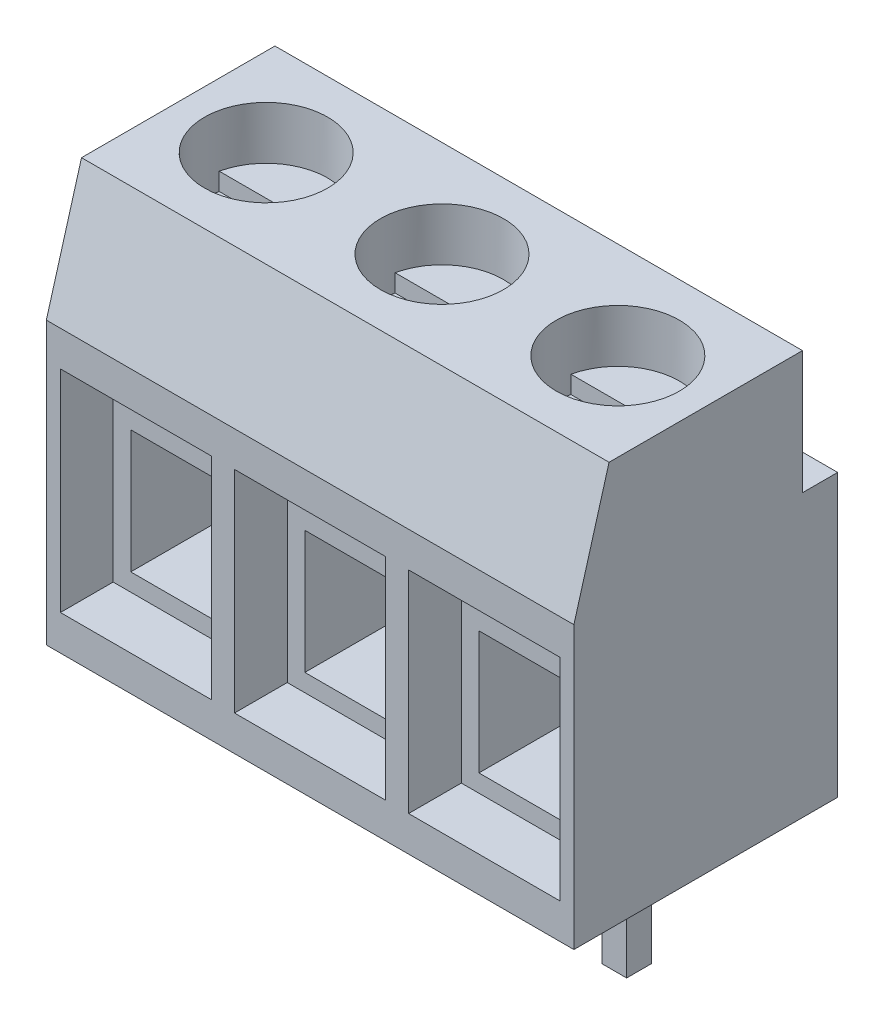
SolidWorks part; units mm, degrees
ref_plane "Front Plane" through (0, 0, 0) normal (0, 0, 1) x (1, 0, 0)
ref_plane "Top Plane" through (0, 0, 0) normal (0, 1, 0) x (1, 0, 0)
ref_plane "Right Plane" through (0, 0, 0) normal (1, 0, 0) x (0, 0, -1)
sketch "Sketch1" plane through (0, 0, 0) normal (0, 1, 0) x (1, 0, 0)
  line L1 (7.5, -3.75) -> (-7.5, -3.75)
  line L2 (7.5, -3.75) -> (7.5, 3.75)
  line L3 (7.5, 3.75) -> (-7.5, 3.75)
  line L4 (-7.5, -3.75) -> (-7.5, 3.75)
  line L5 (7.5, -3.75) -> (-7.5, 3.75) construction
  line L6 (7.5, 3.75) -> (-7.5, -3.75) construction
  point P0 (0, 0)
  dimension "D1" = 15
  dimension "D2" = 7.5
extrude "Boss-Extrude1" add sketch "Sketch1" along normal blind 11.5
sketch "Sketch2" plane through (-7.5, 0, 0) normal (-1, 0, 0) x (0, 0, 1)
  line L1 (-3.75, 11.5) -> (-2.75, 11.5)
  line L2 (-3.75, 11.5) -> (-3.75, 8)
  line L3 (-3.75, 8) -> (-2.75, 8)
  line L4 (-2.75, 11.5) -> (-2.75, 8)
  dimension "D1" = 3.5
  dimension "D2" = 1
extrude "Cut-Extrude1" cut sketch "Sketch2" against normal through all
sketch "Sketch3" plane through (-7.5, 0, 0) normal (-1, 0, 0) x (0, 0, 1)
  line L0 (3.75, 8) -> (2.75, 11.5)
  line L1 (3.75, 11.5) -> (3.75, 0) construction
  line L2 (-2.75, 11.5) -> (3.75, 11.5) construction
  line L4 (-2.75, 8) -> (3.75, 8) construction
  line L5 (2.75, 11.5) -> (3.75, 11.5)
  line L6 (3.75, 11.5) -> (3.75, 8)
  line L7 (-3.75, 8) -> (-2.75, 8) construction
extrude "Cut-Extrude2" cut sketch "Sketch3" against normal through all
sketch "Sketch4" plane through (0, 11.5, 0) normal (0, 1, 0) x (1, 0, 0)
  line L0 (-7.5, 0) -> (-5, 0) construction
  line L1 (-7.5, 2.75) -> (-7.5, -2.75) construction
  line L2 (-5, 0) -> (5, 0) construction
  line L3 (5, 0) -> (7.5, 0) construction
  line L4 (7.5, -2.75) -> (7.5, 2.75) construction
  circle A0 centre (-5, 0) radius 1.75
  circle A1 centre (0, 0) radius 1.75
  circle A2 centre (5, 0) radius 1.75
  dimension "D2" = 3.5
  dimension "D1" = 2.5
extrude "Cut-Extrude3" cut sketch "Sketch4" against normal blind 1.5
sketch "Sketch5" plane through (0, 10, 0) normal (0, 1, 0) x (1, 0, 0)
  line L1 (-6.7093, 0.375) -> (-3.2907, 0.375)
  line L2 (-6.7093, 0.375) -> (-6.7093, -0.375)
  line L3 (-6.7093, -0.375) -> (-3.2907, -0.375)
  line L4 (-3.2907, 0.375) -> (-3.2907, -0.375)
  line L5 (-1.7093, 0.375) -> (1.7093, 0.375)
  line L6 (-1.7093, 0.375) -> (-1.7093, -0.375)
  line L7 (-1.7093, -0.375) -> (1.7093, -0.375)
  line L8 (1.7093, 0.375) -> (1.7093, -0.375)
  line L9 (3.2907, 0.375) -> (6.7093, 0.375)
  line L10 (3.2907, 0.375) -> (3.2907, -0.375)
  line L11 (3.2907, -0.375) -> (6.7093, -0.375)
  line L12 (6.7093, 0.375) -> (6.7093, -0.375)
  circle A1 centre (-5, 0) radius 1.75
  circle A2 centre (-5, 0) radius 1.75
  circle A3 centre (0, 0) radius 1.75
  circle A4 centre (0, 0) radius 1.75
  circle A5 centre (5, 0) radius 1.75
  circle A6 centre (5, 0) radius 1.75
  point P21 (-6.7093, 0)
  circle M14 centre (-5, 0) radius 1.75
  dimension "D4" = 0.75
  dimension "D1" = 0
  dimension "D2" = 0
  dimension "D3" = 0
extrude "Cut-Extrude4" cut sketch "Sketch5" against normal blind 0.5 contours L4 L1 L2 L3 | L2 M14 | L4 M14 | L8 L5 L6 L7 | L8 A4 | L12 L9 L10 L11 | L12 A6 | L10 A6 | L6 A4
sketch "Sketch6" plane through (0, 0, 3.75) normal (0, 0, 1) x (1, 0, 0)
  line L0 (-7.5, 0) -> (7.5, 0) construction
  line L1 (-7.1, 7) -> (-2.8, 7)
  line L2 (-7.1, 7) -> (-7.1, 1)
  line L3 (-7.1, 1) -> (-2.8, 1)
  line L4 (-2.8, 7) -> (-2.8, 1)
  line L5 (-2.15, 7) -> (2.15, 7)
  line L6 (-2.15, 7) -> (-2.15, 1)
  line L7 (-2.15, 1) -> (2.15, 1)
  line L8 (2.15, 7) -> (2.15, 1)
  line L9 (2.8, 7) -> (7.1, 7)
  line L10 (2.8, 7) -> (2.8, 1)
  line L11 (2.8, 1) -> (7.1, 1)
  line L12 (7.1, 7) -> (7.1, 1)
  line L13 (-7.5, 8) -> (-7.5, 0) construction
  line L14 (7.5, 8) -> (7.5, 0) construction
  point P14 (0, 1)
  point P16 (-2.7462, 7)
  point P19 (7.2494, 1)
  dimension "D1" = 6
  dimension "D2" = 1
  dimension "D3" = 4.3
  dimension "D4" = 0.4
  dimension "D5" = 0.4
extrude "Cut-Extrude5" cut sketch "Sketch6" against normal blind 1.5
sketch "Sketch7" plane through (0, 0, 2.25) normal (0, 0, 1) x (1, 0, 0)
  line L0 (-7.1, 1) -> (-2.8, 1) construction
  line L1 (-6.6, 3) -> (-3.3, 3)
  line L2 (-6.6, 3) -> (-6.6, 1.5)
  line L3 (-6.6, 1.5) -> (-3.3, 1.5)
  line L4 (-3.3, 3) -> (-3.3, 1.5)
  line L5 (-1.65, 3) -> (1.65, 3)
  line L6 (-1.65, 3) -> (-1.65, 1.5)
  line L7 (-1.65, 1.5) -> (1.65, 1.5)
  line L8 (1.65, 3) -> (1.65, 1.5)
  line L9 (3.3, 3) -> (6.6, 3)
  line L10 (3.3, 3) -> (3.3, 1.5)
  line L11 (3.3, 1.5) -> (6.6, 1.5)
  line L12 (6.6, 3) -> (6.6, 1.5)
  line L13 (-2.15, 1) -> (2.15, 1) construction
  line L14 (2.8, 1) -> (7.1, 1) construction
  line L15 (-7.1, 7) -> (-7.1, 1) construction
  point P12 (-4.95, 1.5)
  point P15 (-4.95, 1)
  point P16 (0, 1.5)
  point P19 (0, 1)
  point P20 (4.95, 1.5)
  point P23 (4.95, 1)
  point P26 (-3.8, 1.9037)
  dimension "D1" = 1.5
  dimension "D2" = 0.5
  dimension "D3" = 0.5
extrude "Cut-Extrude6" cut sketch "Sketch7" against normal offset from surface (5 mm away) 1 up to face at (0, 4, -3.75)
chamfer "Chamfer1" distance 2 distance2 3 3 edges at (4.95, 3, 2.25) (0, 3, 2.25) (-4.95, 3, 2.25)
sketch "Sketch8" plane through (0, 0, 0) normal (0, -1, 0) x (1, 0, 0)
  line L0 (-7.5, -0.25) -> (-5, -0.25) construction
  line L1 (-7.5, -3.75) -> (-7.5, 3.75) construction
  line L2 (-5, -0.25) -> (0, -0.25) construction
  line L3 (0, -0.25) -> (5, -0.25) construction
  line L4 (5, -0.25) -> (7.5, -0.25) construction
  line L5 (7.5, 3.75) -> (7.5, -3.75) construction
  line L6 (7.5, -3.75) -> (-7.5, -3.75) construction
  line L8 (-5.35, -0.6) -> (-4.65, -0.6)
  line L9 (-5.35, -0.6) -> (-5.35, 0.1)
  line L10 (-5.35, 0.1) -> (-4.65, 0.1)
  line L11 (-4.65, -0.6) -> (-4.65, 0.1)
  line L12 (-5.35, -0.6) -> (-4.65, 0.1) construction
  line L13 (-5.35, 0.1) -> (-4.65, -0.6) construction
  line L14 (-0.35, -0.6) -> (0.35, -0.6)
  line L15 (-0.35, -0.6) -> (-0.35, 0.1)
  line L16 (-0.35, 0.1) -> (0.35, 0.1)
  line L17 (0.35, -0.6) -> (0.35, 0.1)
  line L18 (-0.35, -0.6) -> (0.35, 0.1) construction
  line L19 (-0.35, 0.1) -> (0.35, -0.6) construction
  line L20 (4.65, -0.6) -> (5.35, -0.6)
  line L21 (4.65, -0.6) -> (4.65, 0.1)
  line L22 (4.65, 0.1) -> (5.35, 0.1)
  line L23 (5.35, -0.6) -> (5.35, 0.1)
  line L24 (4.65, -0.6) -> (5.35, 0.1) construction
  line L25 (4.65, 0.1) -> (5.35, -0.6) construction
  dimension "D1" = 2.5
  dimension "D2" = 3.5
  dimension "D3" = 0.7
extrude "Boss-Extrude2" add sketch "Sketch8" along normal blind 3.6
